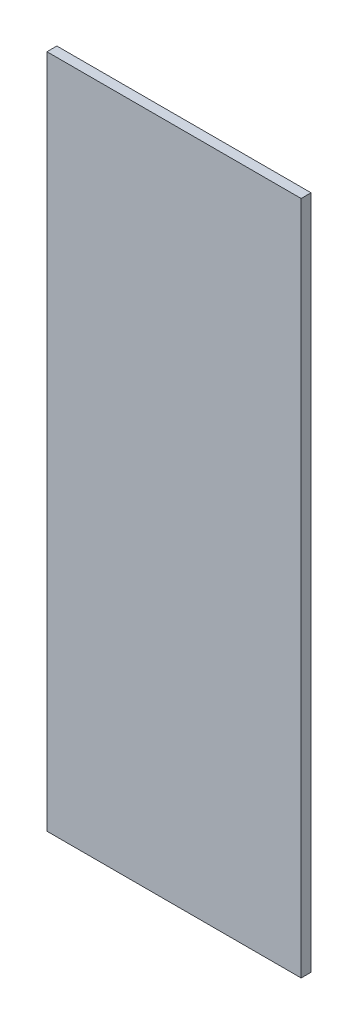
SolidWorks part; units mm, degrees
ref_plane "Front Plane" through (0, 0, 0) normal (0, 0, 1) x (1, 0, 0)
ref_plane "Top Plane" through (0, 0, 0) normal (0, 1, 0) x (1, 0, 0)
ref_plane "Right Plane" through (0, 0, 0) normal (1, 0, 0) x (0, 0, -1)
sketch "Sketch1" plane through (0, 0, 0) normal (0, 0, 1) x (1, 0, 0)
  line L1 (-26.9543, 27.794) -> (24.3781, 27.794)
  line L2 (-26.9543, 27.794) -> (-26.9543, -108.536)
  line L3 (-26.9543, -108.536) -> (24.3781, -108.536)
  line L4 (24.3781, 27.794) -> (24.3781, -108.536)
  dimension "D1" = 51.3324
  dimension "D2" = 136.33
extrude "Boss-Extrude2" add sketch "Sketch1" along normal blind 2
sketch "Sketch14" plane through (0, 0, 2) normal (0, 0, 1) x (1, 0, 0)
  line L0 (-19.2881, 21.794) -> (16.7119, 21.794) construction
  line L1 (16.7119, 21.794) -> (16.7119, -26.206) construction
  line L2 (16.7119, -26.206) -> (-19.2881, -26.206) construction
  line L3 (-19.2881, -26.206) -> (-19.2881, 21.794) construction
  line L4 (24.3781, -108.536) -> (24.3781, 27.794) construction
  line L5 (24.3781, 27.794) -> (-26.9543, 27.794) construction
  line L6 (-26.9543, 27.794) -> (-26.9543, -108.536) construction
  dimension "D1" = 7.6662
  dimension "D2" = 7.6662
  dimension "D3" = 48
  dimension "D4" = 6
